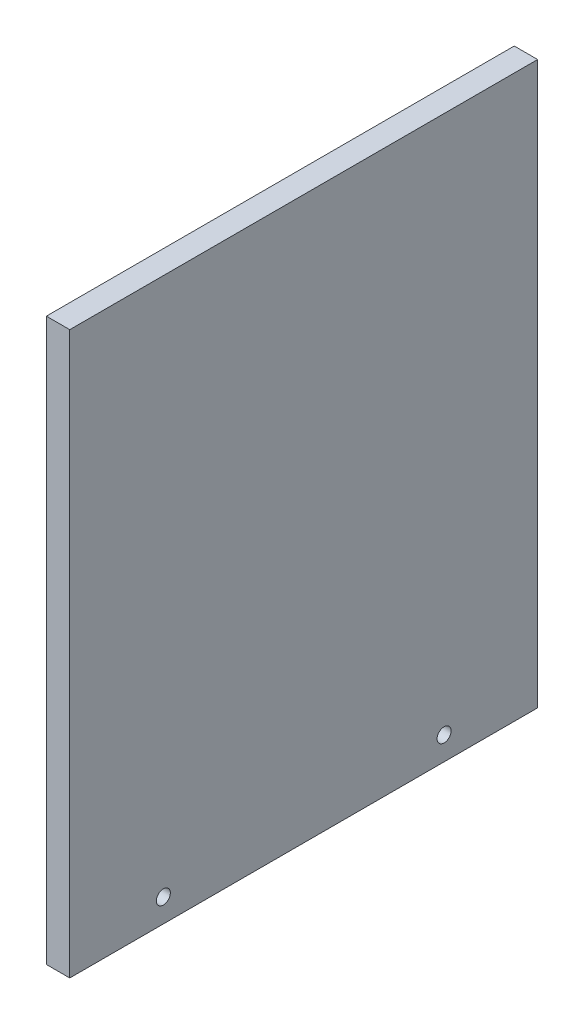
SolidWorks part; units mm, degrees
ref_plane "Front Plane" through (0, 0, 0) normal (0, 0, 1) x (1, 0, 0)
ref_plane "Top Plane" through (0, 0, 0) normal (0, 1, 0) x (1, 0, 0)
ref_plane "Right Plane" through (0, 0, 0) normal (1, 0, 0) x (0, 0, -1)
sketch "Sketch1" plane through (0, 0, 0) normal (1, 0, 0) x (0, 0, -1)
  line L0 (0, 0) -> (100, 0)
  line L1 (100, 0) -> (100, -120)
  line L2 (100, -120) -> (0, -120)
  line L3 (0, -120) -> (0, 0)
extrude "Boss-Extrude1" add sketch "Sketch1" along normal blind 5
sketch "Sketch2" plane through (5, 0, 0) normal (1, 0, 0) x (0, 0, -1)
  line L0 (50, -120) -> (50, -115)
  line L1 (0, -120) -> (100, -120) construction
  line L2 (50, -115) -> (80, -115)
  line L3 (50, -115) -> (20, -115)
  circle A0 centre (20, -115) radius 1.5
  circle A1 centre (80, -115) radius 1.5
extrude "Cut-Extrude1" cut sketch "Sketch2" against normal blind 10 contours A0 | A1
